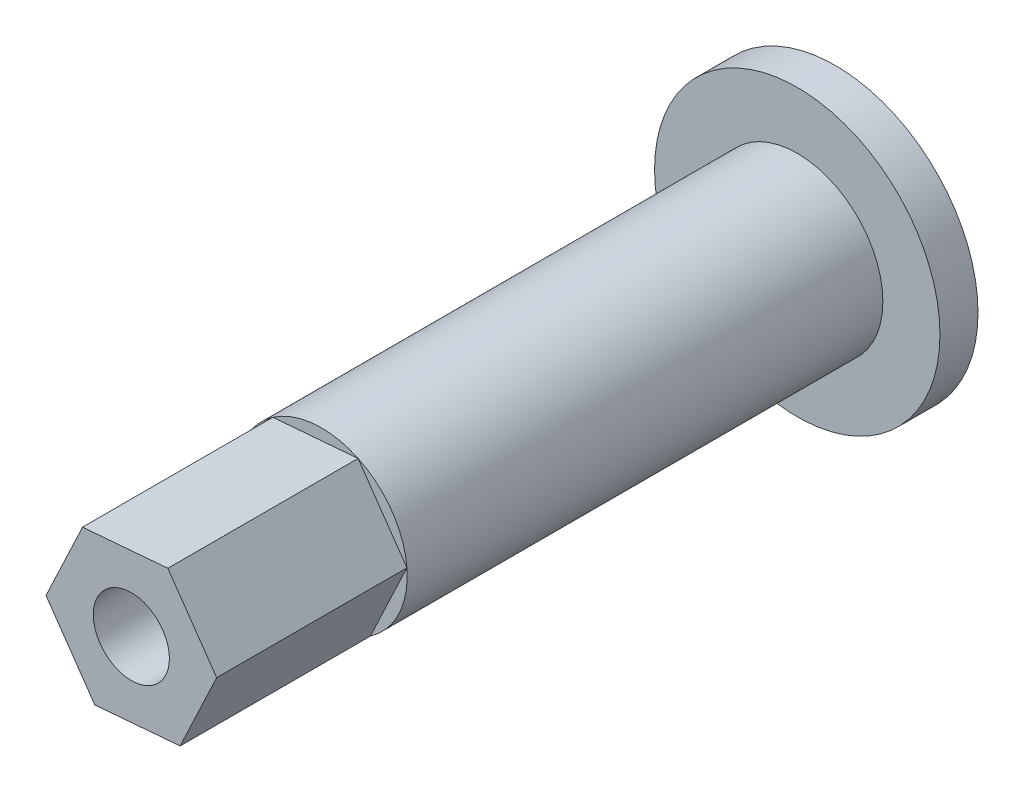
SolidWorks part; units mm, degrees
ref_plane "Front Plane" through (0, 0, 0) normal (0, 0, 1) x (1, 0, 0)
ref_plane "Top Plane" through (0, 0, 0) normal (0, 1, 0) x (1, 0, 0)
ref_plane "Right Plane" through (0, 0, 0) normal (1, 0, 0) x (0, 0, -1)
sketch "Sketch1" plane through (0, 0, 0) normal (0, 0, 1) x (1, 0, 0)
  line L0 (-1.85, 1.9666) -> (-1.85, -1.9666)
  line L1 (1.85, 1.9666) -> (1.85, -1.9666)
  circle A0 centre (0, 0) radius 4.5
  arc A2 (1.8521, 1.9646) -> (1.85, 1.9666) centre (0, 0) ccw
  arc A3 (-1.85, 1.9666) -> (1.8521, 1.9646) centre (0, 0) cw
  arc A4 (1.85, -1.9666) -> (-1.85, -1.9666) centre (0, 0) cw
  dimension "D1" = 9
  dimension "D2" = 3.7
  dimension "D3" = 1.85
extrude "Boss-Extrude1" add sketch "Sketch1" along normal blind 10
sketch "Sketch2" plane through (0, 0, 0) normal (0, 0, -1) x (-1, 0, 0)
  line L0 (-1.85, 1.9666) -> (-1.85, -1.9666) construction
  line L1 (1.85, 1.9666) -> (1.85, -1.9666) construction
  line L2 (1.85, 1.9666) -> (1.85, -1.9666)
  line L3 (-1.85, 1.9666) -> (-1.85, -1.9666)
  circle A0 centre (0, 0) radius 7.5
  arc A1 (1.85, 1.9666) -> (-1.85, 1.9666) centre (0, 0) ccw construction
  arc A2 (-1.85, -1.9666) -> (1.85, -1.9666) centre (0, 0) ccw construction
  arc A3 (-1.85, -1.9666) -> (1.85, -1.9666) centre (0, 0) ccw
  arc A4 (1.85, 1.9666) -> (-1.85, 1.9666) centre (0, 0) ccw
extrude "Boss-Extrude2" add sketch "Sketch2" along normal blind 2 contours A0
sketch "Sketch3" plane through (0, 0, 10) normal (0, 0, 1) x (1, 0, 0)
  circle A0 centre (0, 0) radius 4.5
extrude "Boss-Extrude3" add sketch "Sketch3" along normal blind 15
sketch "Sketch4" plane through (0, 0, 25) normal (0, 0, 1) x (1, 0, 0)
  line L1 (1.9208, 4.0695) -> (-2.5639, 3.6982)
  line L2 (-2.5639, 3.6982) -> (-4.4847, -0.3713)
  line L3 (-4.4847, -0.3713) -> (-1.9208, -4.0695)
  line L4 (-1.9208, -4.0695) -> (2.5639, -3.6982)
  line L5 (2.5639, -3.6982) -> (4.4847, 0.3713)
  line L6 (4.4847, 0.3713) -> (1.9208, 4.0695)
  circle A0 centre (0, 0) radius 3.8971 construction
extrude "Boss-Extrude4" add sketch "Sketch4" along normal blind 10
sketch "Sketch5" plane through (0, 0, 35) normal (0, 0, 1) x (1, 0, 0)
  circle A0 centre (0, 0) radius 2
extrude "Cut-Extrude1" cut sketch "Sketch5" against normal blind 6
